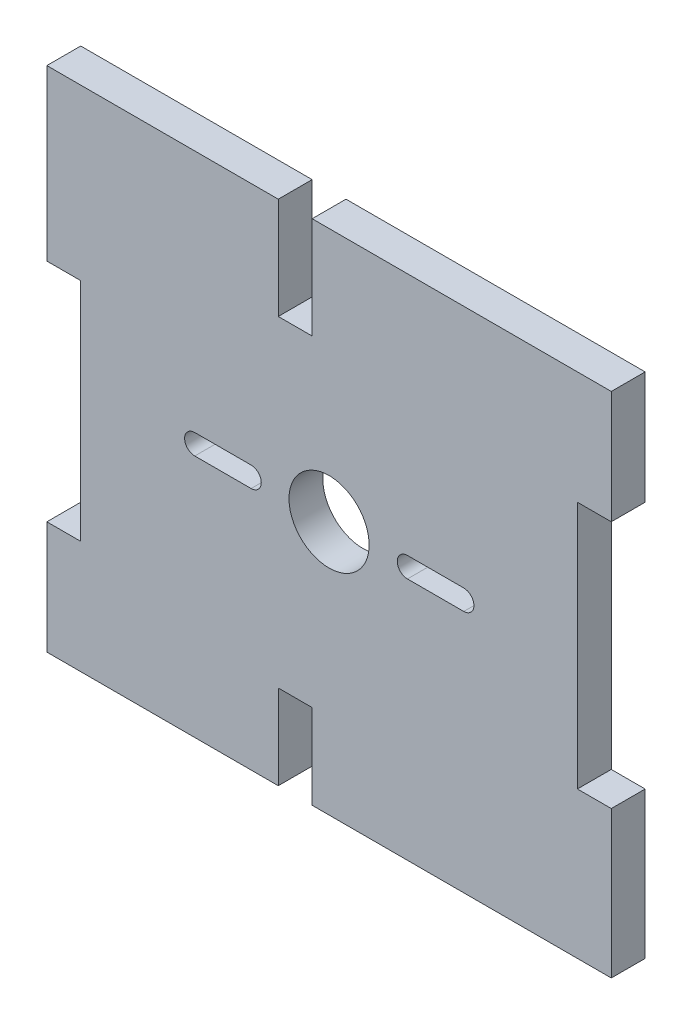
SolidWorks part; units mm, degrees
ref_plane "前视基准面" through (0, 0, 0) normal (0, 0, 1) x (1, 0, 0)
ref_plane "上视基准面" through (0, 0, 0) normal (0, 1, 0) x (1, 0, 0)
ref_plane "右视基准面" through (0, 0, 0) normal (1, 0, 0) x (0, 0, -1)
ref_plane "基准面4" through (0, 0, 3) normal (0, 0, 1) x (1, 0, 0)
sketch "草图1" plane through (0, 0, 3) normal (0, 0, 1) x (1, 0, 0)
  line L0 (9.2367, 23.399) -> (14.2266, 23.399)
  line L1 (14.2266, 21.5995) -> (9.2367, 21.5995)
  line L2 (46.1319, 44.9999) -> (19.6324, 44.9999)
  line L3 (19.6324, 44.9999) -> (19.6324, 35.9998)
  line L4 (19.6324, 35.9998) -> (16.6324, 35.9998)
  line L5 (16.6324, 35.9998) -> (16.6324, 44.9999)
  line L6 (16.6324, 44.9999) -> (-3.8674, 44.9999)
  line L7 (-3.8674, 44.9999) -> (-3.8674, 29.9998)
  line L8 (-3.8674, 29.9998) -> (-0.8673, 29.9998)
  line L9 (-0.8673, 29.9998) -> (-0.8673, 9.9991)
  line L10 (-0.8673, 9.9991) -> (-3.8674, 9.9991)
  line L11 (-3.8674, 9.9991) -> (-3.8674, 0)
  line L12 (-3.8674, 0) -> (16.6324, 0)
  line L13 (16.6324, 0) -> (16.6324, 7.4993)
  line L14 (16.6324, 7.4993) -> (19.6324, 7.4993)
  line L15 (19.6324, 7.4993) -> (19.6324, 0)
  line L16 (19.6324, 0) -> (46.1319, 0)
  line L17 (46.1319, 0) -> (46.1319, 13.0005)
  line L18 (46.1319, 13.0005) -> (43.1319, 13.0005)
  line L19 (43.1319, 13.0005) -> (43.1319, 34.9994)
  line L20 (43.1319, 34.9994) -> (46.1319, 34.9994)
  line L21 (46.1319, 34.9994) -> (46.1319, 44.9999)
  line L22 (33.0644, 21.5871) -> (28.0745, 21.5871)
  line L23 (28.0745, 23.3866) -> (33.0644, 23.3866)
  arc A0 (14.2266, 23.399) -> (14.2266, 21.5995) centre (14.2266, 22.4993) cw
  arc A1 (9.2367, 21.5995) -> (9.2367, 23.399) centre (9.2367, 22.4993) cw
  arc A2 (33.0644, 23.3866) -> (33.0644, 21.5871) centre (33.0644, 22.4869) cw
  arc A3 (28.0745, 21.5871) -> (28.0745, 23.3866) centre (28.0745, 22.4869) cw
  circle A4 centre (21.1317, 22.4992) radius 3.55
extrude "凸台-拉伸1" add sketch "草图1" against normal blind 3
